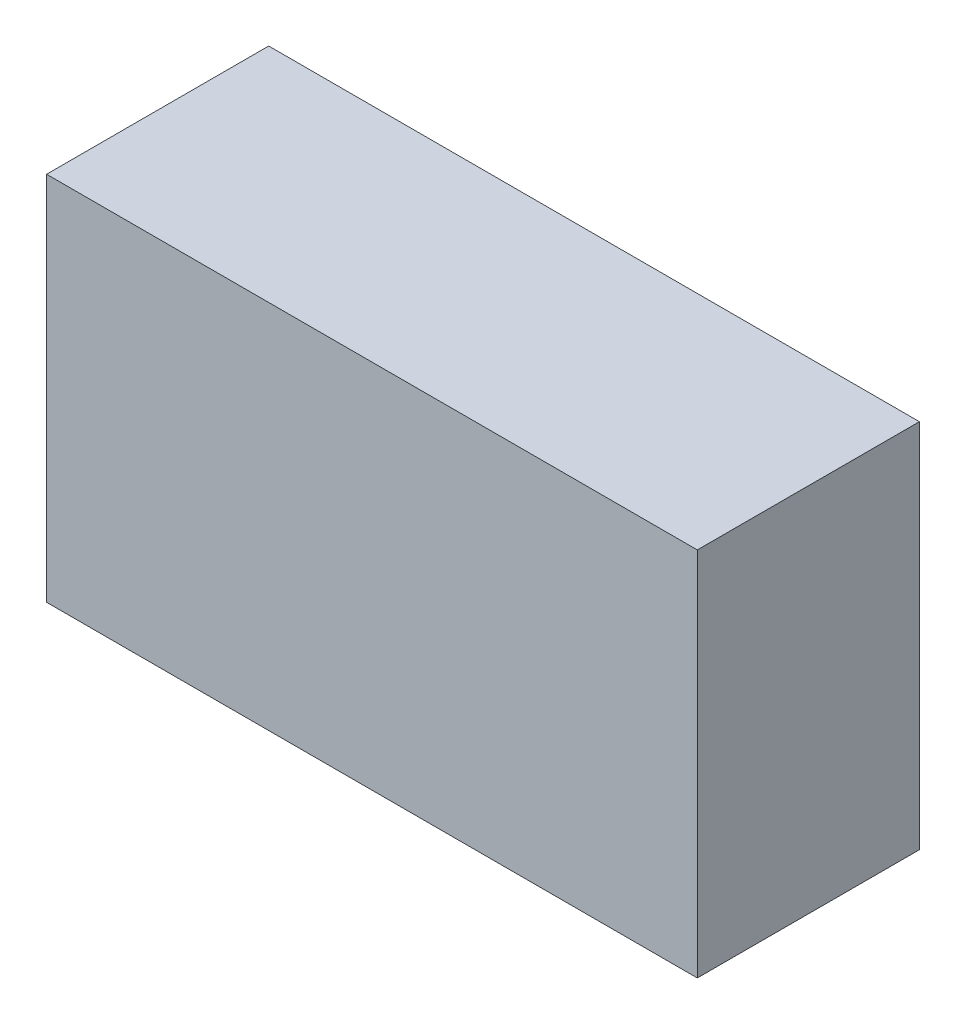
SolidWorks part; units mm, degrees
ref_plane "Front Plane" through (0, 0, 0) normal (0, 0, 1) x (1, 0, 0)
ref_plane "Top Plane" through (0, 0, 0) normal (0, 1, 0) x (1, 0, 0)
ref_plane "Right Plane" through (0, 0, 0) normal (1, 0, 0) x (0, 0, -1)
sketch "Sketch1" plane through (0, 0, 0) normal (0, 0, 1) x (1, 0, 0)
  line L0 (-19.9755, 77.7714) -> (-41.6155, 77.7714) construction
  line L1 (-41.4155, 77.5714) -> (-20.1755, 77.5714)
  line L2 (-41.4155, 77.5714) -> (-41.4155, 65.47)
  line L3 (-41.4155, 65.47) -> (-20.1755, 65.47)
  line L4 (-20.1755, 77.5714) -> (-20.1755, 65.47)
  line L5 (-19.9755, 77.7714) -> (-19.9755, 65.27) construction
  line L6 (-19.9755, 65.27) -> (-41.6155, 65.27) construction
  line L7 (-41.6155, 65.27) -> (-41.6155, 77.7714) construction
  dimension "D1" = 0.2
  dimension "D2" = 0.2
  dimension "D3" = 0.2
  dimension "D4" = 0.2
extrude "Boss-Extrude1" add sketch "Sketch1" along normal blind 7.25
shell "Shell1" thickness 0.5
equation "\"D2@Sketch1\"=\"D1@Sketch1\""
equation "\"D3@Sketch1\"=\"D1@Sketch1\""
equation "\"D4@Sketch1\"=\"D1@Sketch1\""
